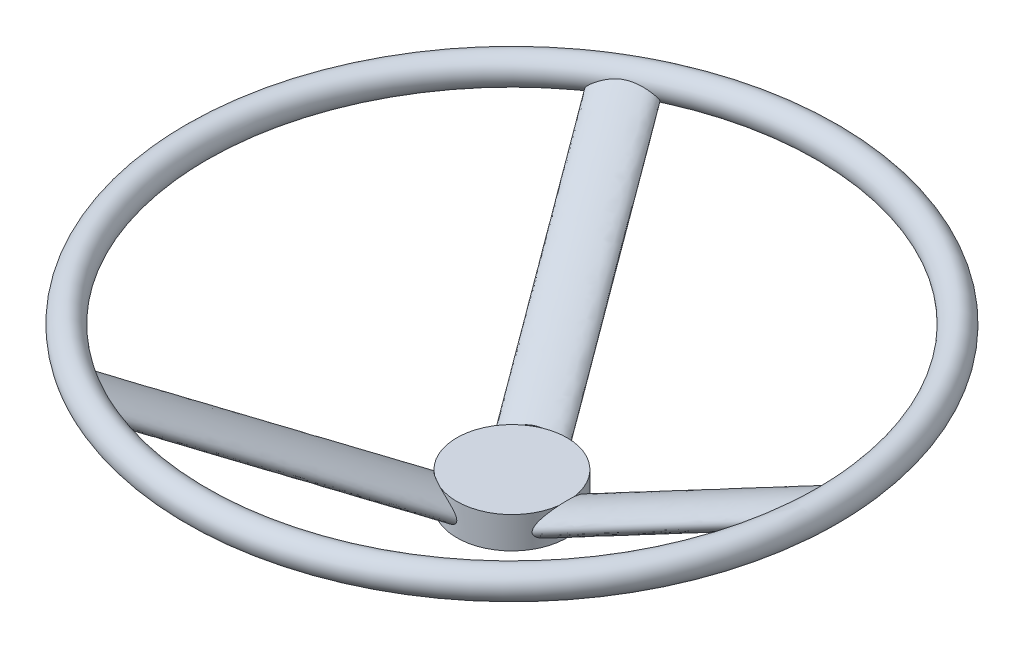
SolidWorks part; units mm, degrees
ref_plane "Front Plane" through (0, 0, 0) normal (0, 0, 1) x (1, 0, 0)
ref_plane "Top Plane" through (0, 0, 0) normal (0, 1, 0) x (1, 0, 0)
ref_plane "Right Plane" through (0, 0, 0) normal (1, 0, 0) x (0, 0, -1)
sketch "Sketch1" plane through (0, 0, 0) normal (0, 0, 1) x (1, 0, 0)
  line L1 (0, 0) -> (52.5, 0)
  line L2 (0, 0) -> (0, 30)
  line L3 (0, 30) -> (52.5, 30)
  line L4 (52.5, 0) -> (52.5, 30)
  circle A0 centre (300, 150) radius 13.75
  dimension "D1" = 150
  dimension "D5" = 27.5
  dimension "D2" = 30
  dimension "D3" = 52.5
  dimension "D4" = 300
revolve "Revolve1" add sketch "Sketch1" angle 360 about L2
sketch "Sketch2" plane through (0, 0, 0) normal (0, 0, 1) x (1, 0, 0)
  line L0 (300, 149.3681) -> (52.5, 18)
  line L1 (52.5, 0) -> (52.5, 30) construction
  dimension "D1" = 12
ref_plane "Plane1" through (300, 149.3681, 0) normal (-0.8833, -0.4688, 0) x (0, 0, 1)
sketch "Sketch3" plane through (300, 149.3681, 0) normal (-0.8833, -0.4688, 0) x (0, 0, 1)
  ellipse E0 centre (0, 0.0221) end of major axis (26.25, 0.0221) minor radius 11.25
  dimension "D1" = 26.25
  dimension "D2" = 11.25
extrude "Boss-Extrude1" add sketch "Sketch3" along normal up to surface (288.1545 mm away)
pattern_circular "CirPattern1" count 3 over 360 about axis through (0, 0, 0) along (0, -1, 0) of "Boss-Extrude1"
